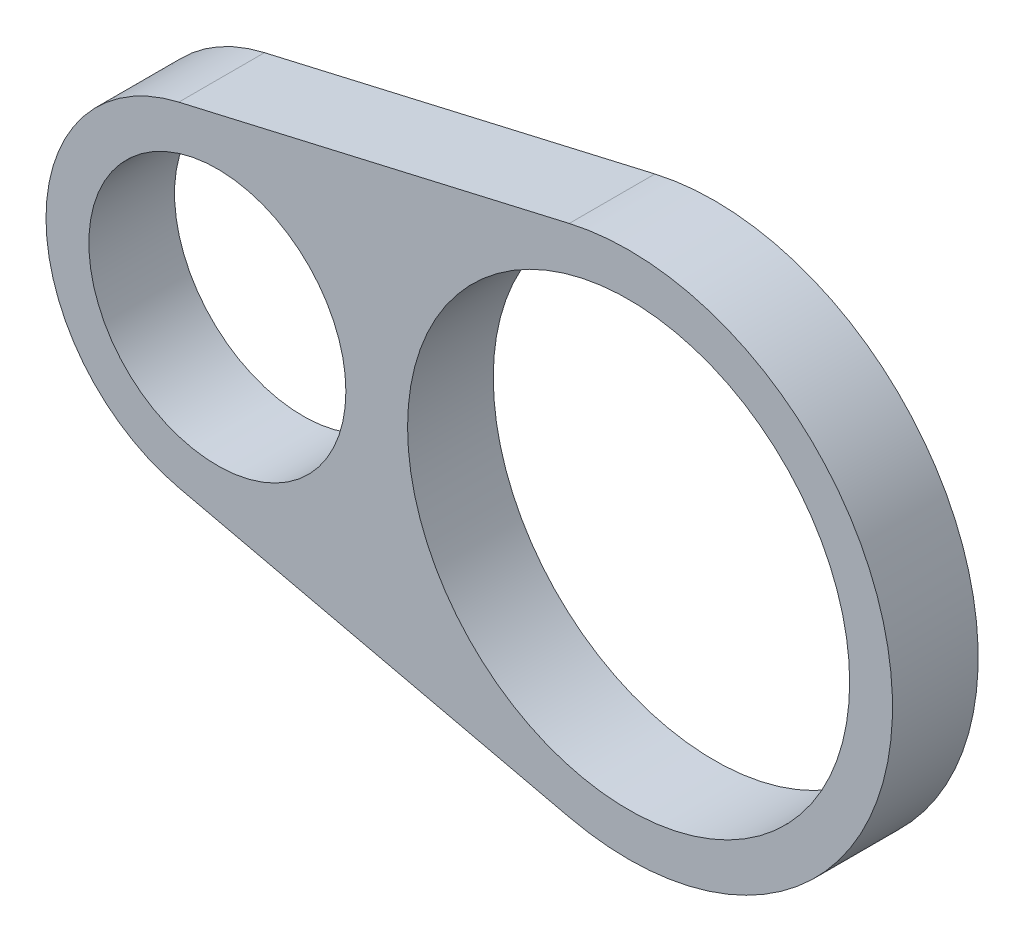
SolidWorks part; units mm, degrees
ref_plane "Plano frontal" through (0, 0, 0) normal (0, 0, 1) x (1, 0, 0)
ref_plane "Plano superior" through (0, 0, 0) normal (0, 1, 0) x (1, 0, 0)
ref_plane "Plano direito" through (0, 0, 0) normal (1, 0, 0) x (0, 0, -1)
sketch "Esboço2" plane through (0, 0, 0) normal (0, 0, 1) x (1, 0, 0)
  line L0 (-24, 0) -> (24, 0) construction
  line L1 (-28.5, 19.4872) -> (17.07, 30.0102)
  line L2 (-28.5, -19.4872) -> (17.07, -30.0102)
  circle A0 centre (24, 0) radius 25.8
  circle A1 centre (-24, 0) radius 15
  arc A2 (-5.715, 8.103) -> (-5.715, -8.103) centre (-24, 0) ccw
  arc A3 (-5.715, -8.103) -> (-5.715, 8.103) centre (24, 0) ccw
  circle A4 centre (24, 0) radius 30.8 construction
  circle A5 centre (-24, 0) radius 20 construction
  point P4 (0, 0)
  dimension "D1" = 5
extrude "Ressalto-extrusão1" add sketch "Esboço2" along normal blind 10
